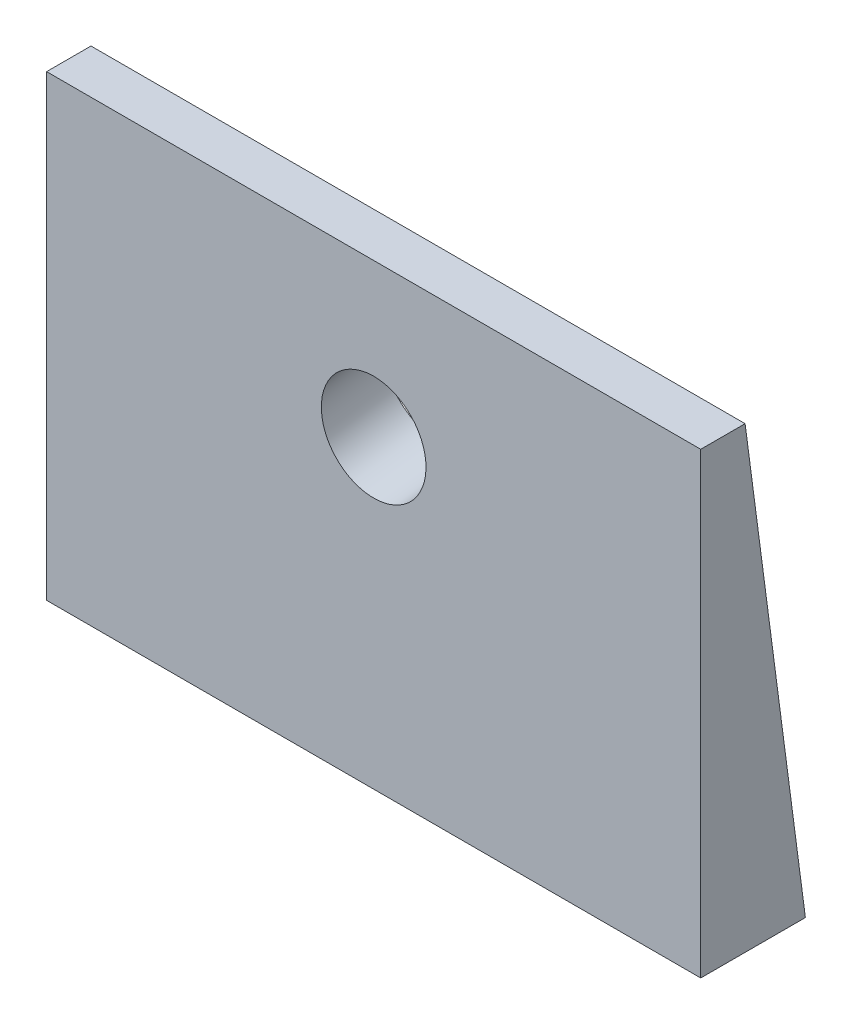
SolidWorks part; units mm, degrees
ref_plane "Front Plane" through (0, 0, 0) normal (0, 0, 1) x (1, 0, 0)
ref_plane "Top Plane" through (0, 0, 0) normal (0, 1, 0) x (1, 0, 0)
ref_plane "Right Plane" through (0, 0, 0) normal (1, 0, 0) x (0, 0, -1)
sketch "Sketch7" plane through (0, 0, 0) normal (1, 0, 0) x (0, 0, -1)
  line L0 (0, 6.47) -> (-40, 6.47)
  line L1 (55, 0) -> (-55, 0) construction
  line L2 (-40, 6.47) -> (-40, 181.47)
  line L3 (-40, 181.47) -> (-23.0392, 181.47)
  line L4 (-23.0392, 181.47) -> (0, 6.47)
  dimension "D1" = 97.5
  dimension "D2" = 40
  dimension "D3" = 175
  dimension "D4" = 6.47
extrude "Boss-Extrude2" add sketch "Sketch7" along normal mid plane 250 separate body
ref_plane "Plane1" through (0, 0.8934, -6.7859) normal (0, 0.1305, -0.9914) x (-1, 0, 0)
sketch "Sketch9" plane through (0, 0.8934, -6.7859) normal (0, 0.1305, -0.9914) x (-1, 0, 0)
  line L0 (0, 55) -> (0, -55) construction
  circle A0 centre (0, 127.16) radius 20
  dimension "D2" = 40
  dimension "D1" = 127.16
extrude "Cut-Extrude1" cut sketch "Sketch9" against normal through all both and the other way through all
equation "\"`15\"=153.387"
